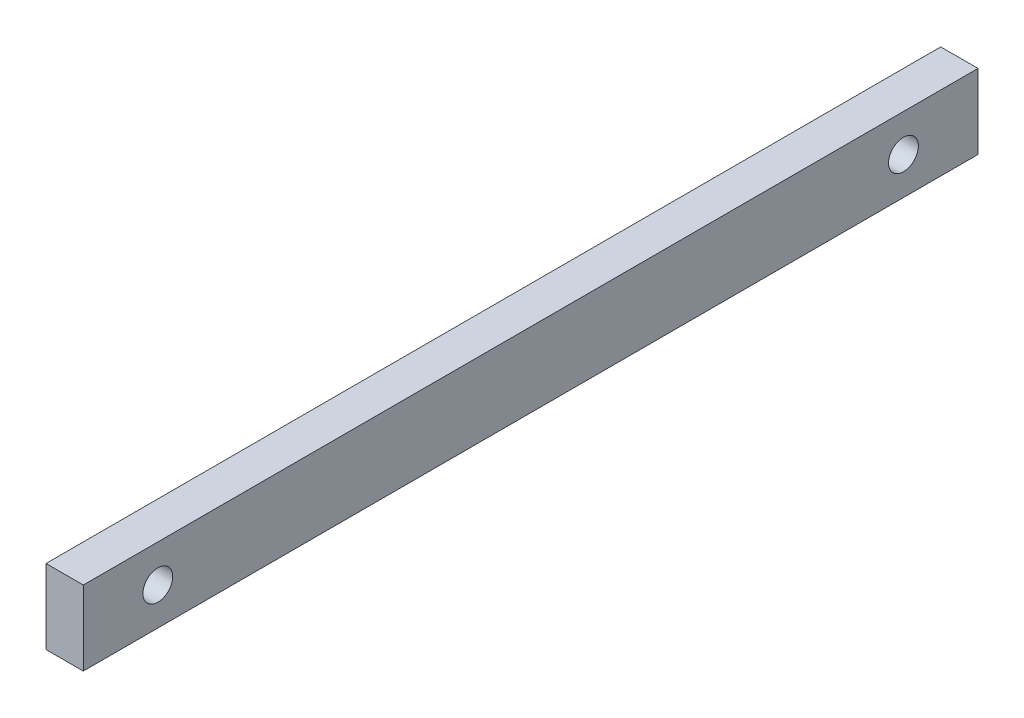
SolidWorks part; units mm, degrees
ref_plane "前视基准面" through (0, 0, 0) normal (0, 0, 1) x (1, 0, 0)
ref_plane "上视基准面" through (0, 0, 0) normal (0, 1, 0) x (1, 0, 0)
ref_plane "右视基准面" through (0, 0, 0) normal (1, 0, 0) x (0, 0, -1)
sketch "草图2" plane through (0, 0, 0) normal (1, 0, 0) x (0, 0, -1)
  line L0 (-60, 0) -> (60, 0)
  line L1 (-60, 5) -> (60, 5)
  line L2 (-60, 5) -> (-60, -5)
  line L3 (-60, -5) -> (60, -5)
  line L4 (60, 5) -> (60, -5)
  line L5 (-60, 5) -> (60, -5) construction
  line L6 (-60, -5) -> (60, 5) construction
  line L7 (-50, 0) -> (50, 0)
  circle A0 centre (-50, 0) radius 2
  circle A1 centre (50, 0) radius 2
  point P0 (0, 0)
  dimension "D1" = 120
  dimension "D2" = 10
  dimension "D3" = 100
  dimension "D4" = 10
extrude "凸台-拉伸1" add sketch "草图2" along normal blind 5 contours L2 L1 L4 L3 | A0 | A1
